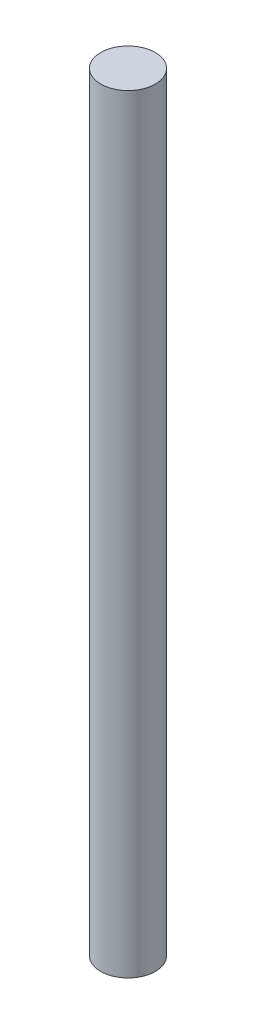
SolidWorks part; units mm, degrees
ref_plane "Front Plane" through (0, 0, 0) normal (0, 0, 1) x (1, 0, 0)
ref_plane "Top Plane" through (0, 0, 0) normal (0, 1, 0) x (1, 0, 0)
ref_plane "Right Plane" through (0, 0, 0) normal (1, 0, 0) x (0, 0, -1)
sketch "Çizim1" plane through (0, 0, 0) normal (0, 1, 0) x (1, 0, 0)
  circle A0 centre (0, 0) radius 1.6
  dimension "D1" = 3.2
extrude "Yükseklik-Ekstrüzyon1" add sketch "Çizim1" along normal blind 45
